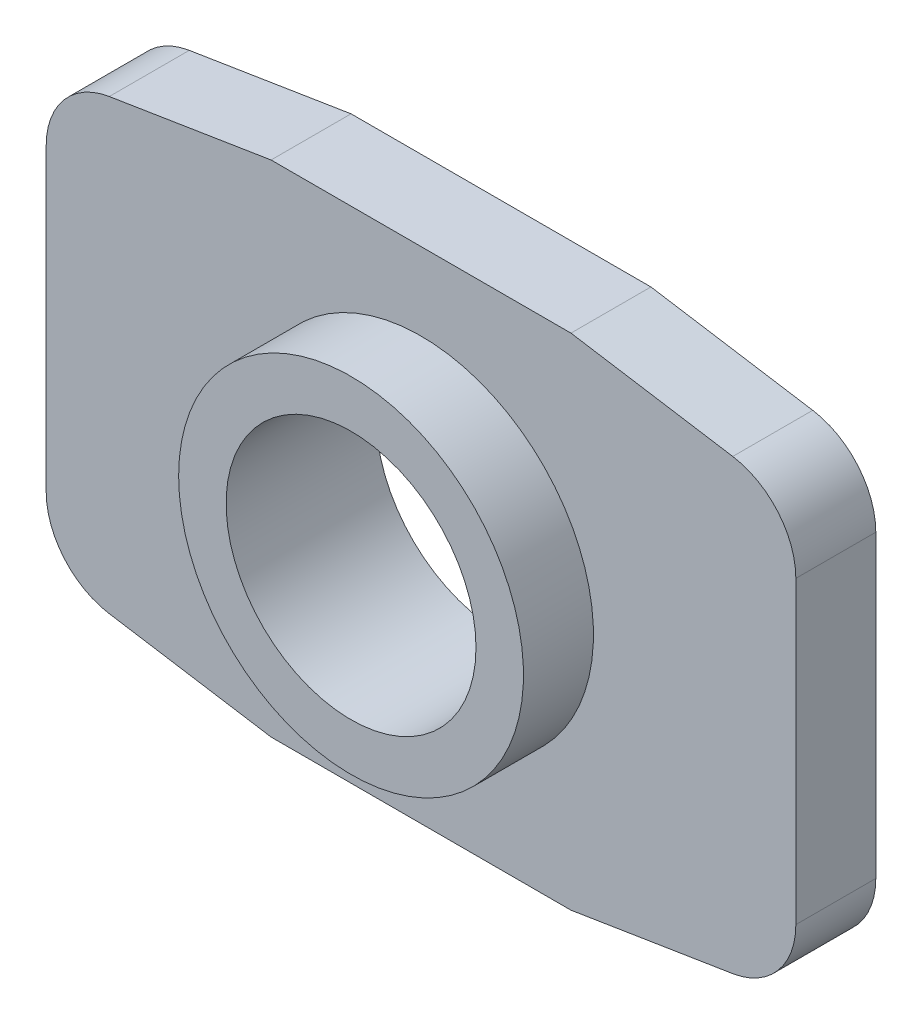
SolidWorks part; units mm, degrees
material "Plain Carbon Steel"
ref_plane "Front Plane" through (0, 0, 0) normal (0, 0, 1) x (1, 0, 0)
ref_plane "Top Plane" through (0, 0, 0) normal (0, 1, 0) x (1, 0, 0)
ref_plane "Right Plane" through (0, 0, 0) normal (1, 0, 0) x (0, 0, -1)
sketch "Sketch1" plane through (0, 0, 0) normal (0, 0, 1) x (1, 0, 0)
  line L0 (-7.5, 0) -> (7.5, 0) construction
  line L1 (-6.2374, 4.4811) -> (-3, 5)
  line L2 (-7.5, -3) -> (-7.5, 3)
  line L3 (-3, 5) -> (3, 5)
  line L4 (7.5, -3) -> (7.5, 3)
  line L5 (0, 5) -> (0, 0) construction
  line L6 (6.2374, 4.4811) -> (3, 5)
  line L7 (6.2374, -4.4811) -> (3, -5)
  line L8 (-3, -5) -> (3, -5)
  line L9 (-6.2374, -4.4811) -> (-3, -5)
  arc A0 (7.5, 3) -> (6.2374, 4.4811) centre (6, 3) ccw
  arc A1 (-7.5, -3) -> (-6.2374, -4.4811) centre (-6, -3) ccw
  arc A2 (7.5, -3) -> (6.2374, -4.4811) centre (6, -3) cw
  arc A3 (-7.5, 3) -> (-6.2374, 4.4811) centre (-6, 3) cw
  dimension "D3" = 6
  dimension "D5" = 1.5
  dimension "D1" = 15
  dimension "D2" = 10
  dimension "D4" = 6
extrude "Boss-Extrude1" add sketch "Sketch1" along normal blind 1.6
sketch "Sketch2" plane through (0, 0, 1.6) normal (0, 0, 1) x (1, 0, 0)
  line L0 (-7.5, 0) -> (0, 0) construction
  line L1 (-7.5, 3) -> (-7.5, -3) construction
  line L2 (0, 0) -> (0, 5) construction
  line L4 (3, 5) -> (-3, 5) construction
  circle A0 centre (0, 0) radius 3.45
  dimension "D2" = 6.9
extrude "Boss-Extrude2" add sketch "Sketch2" along normal blind 1.4
hole_wizard "M6x1.0 Tapped Hole1" positions "Sketch4" profile "Sketch3" tap size "M6x1.0" standard "ANSI Metric" end condition through all
sketch "Sketch4" plane through (0, 0, 3) normal (0, 0, 1) x (1, 0, 0)
  point P0 (0, 0)
sketch "Sketch3" plane through (0, 0, 3) normal (1, 0, 0) x (0, -1, 0)
  line L0 (0, 0) -> (0, 3)
  line L1 (0, 3) -> (2.5, 3)
  line L2 (2.5, 3) -> (2.5, 0)
  line L5 (2.5, 0) -> (0, 0)
  line L11 (0, -6.35) -> (0, 107.95) construction
  dimension "Thread Major Dia." = 5
  dimension "Thru Tap Drill Depth" = 3
